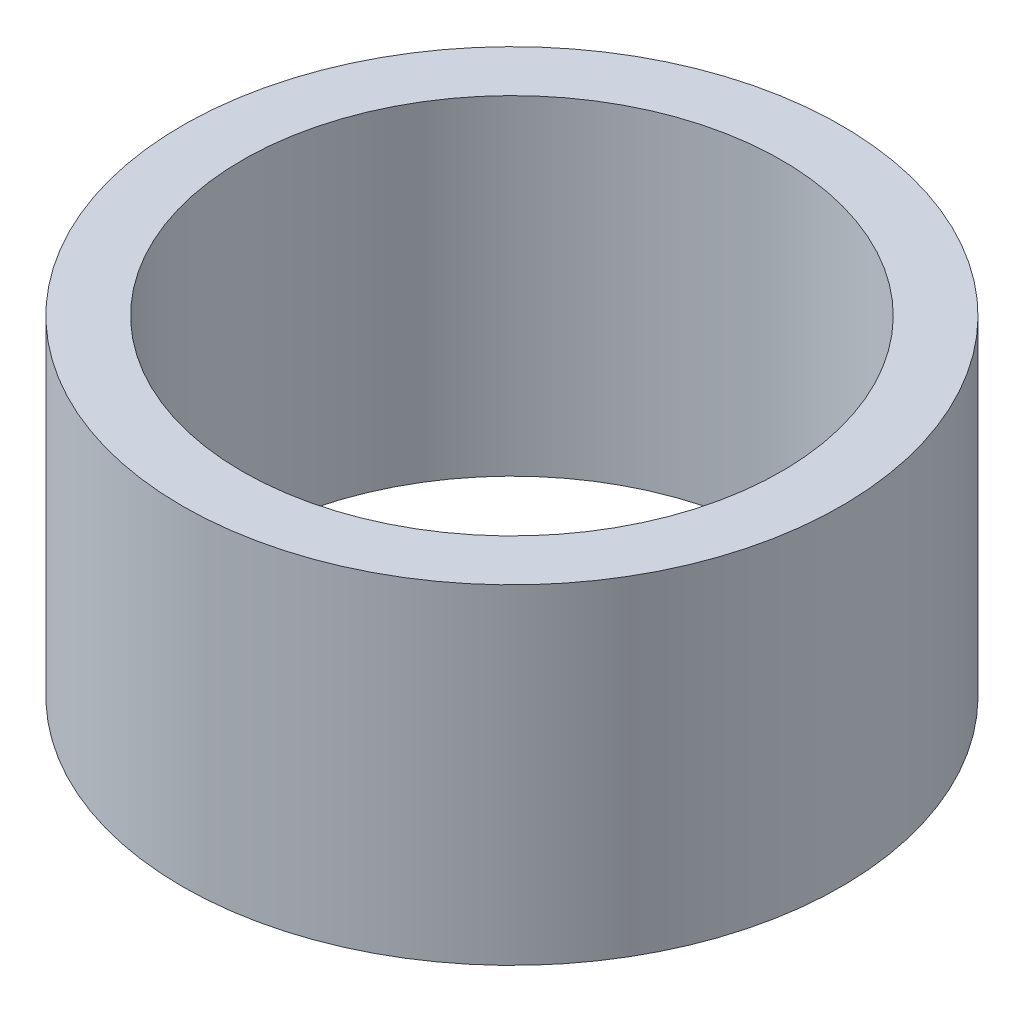
SolidWorks part; units mm, degrees
ref_plane "Front" through (0, 0, 0) normal (0, 0, 1) x (1, 0, 0)
ref_plane "Top" through (0, 0, 0) normal (0, 1, 0) x (1, 0, 0)
ref_plane "Right" through (0, 0, 0) normal (1, 0, 0) x (0, 0, -1)
sketch "Sketch1" plane through (0, 0, 0) normal (0, 1, 0) x (1, 0, 0)
  circle A0 centre (0, 0) radius 9
  circle A1 centre (0, 0) radius 11
  dimension "D2" = 22
  dimension "D1" = 2
extrude "Boss-Extrude1" add sketch "Sketch1" along normal blind 11
